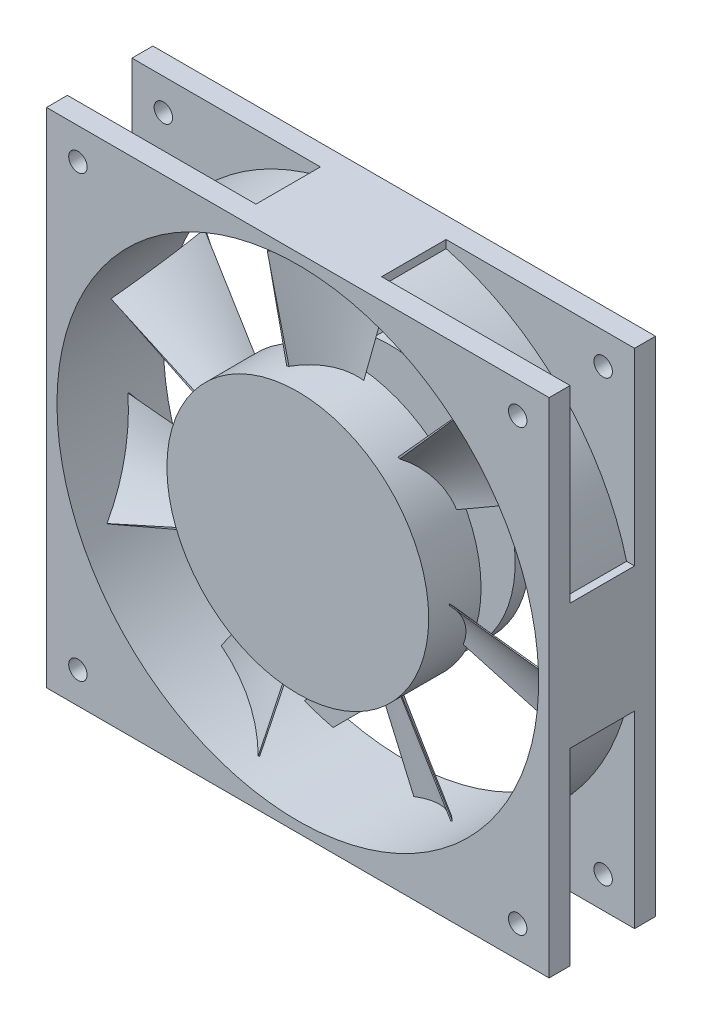
SolidWorks part; units mm, degrees
ref_plane "Front" through (0, 0, 0) normal (0, 0, 1) x (1, 0, 0)
ref_plane "Top" through (0, 0, 0) normal (0, 1, 0) x (1, 0, 0)
ref_plane "Right" through (0, 0, 0) normal (1, 0, 0) x (0, 0, -1)
sketch "Sketch1" plane through (0, 0, 0) normal (0, 0, 1) x (1, 0, 0)
  circle A0 centre (0, 0) radius 60
  dimension "D1" = 120
extrude "Extrude1" add sketch "Sketch1" along normal mid plane 25.4
sketch "Sketch2" plane through (0, 0, 12.7) normal (0, 0, 1) x (1, 0, 0)
  line L1 (-60, -60) -> (60, -60)
  line L2 (-60, -60) -> (-60, 60)
  line L3 (-60, 60) -> (60, 60)
  line L4 (60, -60) -> (60, 60)
  circle A0 centre (0, 0) radius 60 construction
extrude "Extrude2" add sketch "Sketch2" against normal blind 5
sketch "Sketch3" plane through (0, 0, -12.7) normal (0, 0, -1) x (-1, 0, 0)
  line L1 (-60, -60) -> (60, -60)
  line L2 (-60, -60) -> (-60, 60)
  line L3 (-60, 60) -> (60, 60)
  line L4 (60, -60) -> (60, 60)
extrude "Extrude3" add sketch "Sketch3" against normal blind 5
sketch "Sketch4" plane through (-60, 0, 0) normal (-1, 0, 0) x (0, 0, 1)
  line L0 (-12.7, -60) -> (-12.7, 60) construction
  line L1 (-12.7, -15) -> (12.7, -15)
  line L2 (-12.7, -15) -> (-12.7, 15)
  line L3 (-12.7, 15) -> (12.7, 15)
  line L4 (12.7, -15) -> (12.7, 15)
  line L5 (12.7, 60) -> (12.7, -60) construction
  dimension "D1" = 15
  dimension "D2" = 15
extrude "Extrude4" add sketch "Sketch4" against normal up to vertex (120 mm away)
sketch "Sketch5" plane through (0, -60, 0) normal (0, -1, 0) x (1, 0, 0)
  line L0 (-60, 12.7) -> (60, 12.7) construction
  line L1 (-15, 12.7) -> (15, 12.7)
  line L2 (-15, 12.7) -> (-15, -12.7)
  line L3 (-15, -12.7) -> (15, -12.7)
  line L4 (15, 12.7) -> (15, -12.7)
  line L5 (60, -12.7) -> (-60, -12.7) construction
  dimension "D1" = 15
  dimension "D2" = 15
extrude "Extrude5" add sketch "Sketch5" against normal up to vertex (120 mm away)
sketch "Sketch6" plane through (0, 0, -12.7) normal (0, 0, -1) x (-1, 0, 0)
  circle A0 centre (0, 0) radius 57.5
  dimension "D1" = 115
extrude "Cut-Extrude1" cut sketch "Sketch6" against normal through all
sketch "Sketch7" plane through (0, 0, -12.7) normal (0, 0, -1) x (-1, 0, 0)
  circle A0 centre (0, 0) radius 30
  dimension "D1" = 60
extrude "Extrude6" add sketch "Sketch7" against normal blind 3.5
sketch "Sketch8" plane through (0, 0, -12.7) normal (0, 0, -1) x (-1, 0, 0)
  line L0 (21.2132, -21.2132) -> (55.8993, 13.4729)
  line L1 (29.7745, -3.6717) -> (53.7833, 20.3372)
  line L2 (-60, -60) -> (60, -60) construction
  circle A0 centre (0, 0) radius 30 construction
  circle A1 centre (0, 0) radius 57.5 construction
  arc A2 (55.8993, 13.4729) -> (53.7833, 20.3372) centre (0, 0) ccw
  arc A3 (21.2132, -21.2132) -> (29.7745, -3.6717) centre (0, 0) ccw
  dimension "D1" = 6.35
  dimension "D2" = 45
extrude "Extrude7" add sketch "Sketch8" against normal blind 3.5
ref_axis "Axis1" through (0, 0, -9.2) along (0, 0, -1)
pattern_circular "CirPattern1" count 4 over 360 about axis through (0, 0, 0) along (0, 0, 1) of "Extrude7"
sketch "Sketch9" plane through (0, 0, -9.2) normal (0, 0, 1) x (1, 0, 0)
  circle A0 centre (0, 0) radius 5
  dimension "D1" = 10
extrude "Extrude8" add sketch "Sketch9" along normal up to vertex (21.9 mm away)
sketch "Sketch10" plane through (0, 0, 12.7) normal (0, 0, 1) x (1, 0, 0)
  circle A0 centre (0, 0) radius 31.25
  dimension "D1" = 62.5
extrude "Extrude9" add sketch "Sketch10" against normal blind 12.5
ref_plane "Plane1" through (0, 30, 0) normal (0, 1, 0) x (-1, 0, 0)
sketch "Sketch11" plane through (0, 30, 0) normal (0, 1, 0) x (-1, 0, 0)
  line L0 (-60, 12.7) -> (60, 12.7) construction
  line L1 (-31.25, 0.2) -> (31.25, 0.2) construction
  line L2 (-5, 2.2) -> (-2.7022, 2.197)
  line L3 (7, 7.7) -> (7.4472, 7.8174)
  arc A0 (-5, 2.2) -> (7, 7.7) centre (-5.7436, 19.6633) ccw
  arc A1 (-2.7022, 2.197) -> (7.4472, 7.8174) centre (-5.7436, 19.6633) ccw
  dimension "D1" = 5
  dimension "D2" = 2
  dimension "D3" = 5
  dimension "D4" = 7
  dimension "D5" = 0.25
ref_plane "Plane2" through (0, 53, 0) normal (0, 1, 0) x (-1, 0, 0)
sketch "Sketch12" plane through (0, 53, 0) normal (0, 1, 0) x (-1, 0, 0)
  line L0 (11.1326, 8.8423) -> (10.9661, 9.0287)
  line L1 (-9.4633, -0.5246) -> (-9.427, -0.772)
  arc A0 (11.1326, 8.8423) -> (-9.427, -0.772) centre (-15.1586, 38.2749) cw
  arc A1 (10.9661, 9.0287) -> (-9.4633, -0.5246) centre (-15.1586, 38.2749) cw
  dimension "D1" = 0.25
loft "Loft1" add profiles "Sketch11", "Sketch12"
pattern_circular "CirPattern2" count 7 over 360 about axis through (0, 0, -9.2) along (0, 0, -1) of "Loft1"
sketch "Sketch13" plane through (0, 0, 12.7) normal (0, 0, 1) x (1, 0, 0)
  line L0 (52.5, 52.5) -> (-52.5, -52.5) construction
  line L1 (-52.5, -52.5) -> (52.5, -52.5) construction
  line L2 (-52.5, -52.5) -> (-52.5, 52.5) construction
  line L3 (-52.5, 52.5) -> (52.5, 52.5) construction
  line L4 (52.5, -52.5) -> (52.5, 52.5) construction
  circle A0 centre (-52.5, 52.5) radius 2.2
  circle A1 centre (-52.5, -52.5) radius 2.2
  circle A2 centre (52.5, -52.5) radius 2.2
  circle A3 centre (52.5, 52.5) radius 2.2
  dimension "D2" = 4.4
  dimension "D1" = 105
extrude "Cut-Extrude2" cut sketch "Sketch13" against normal through all
